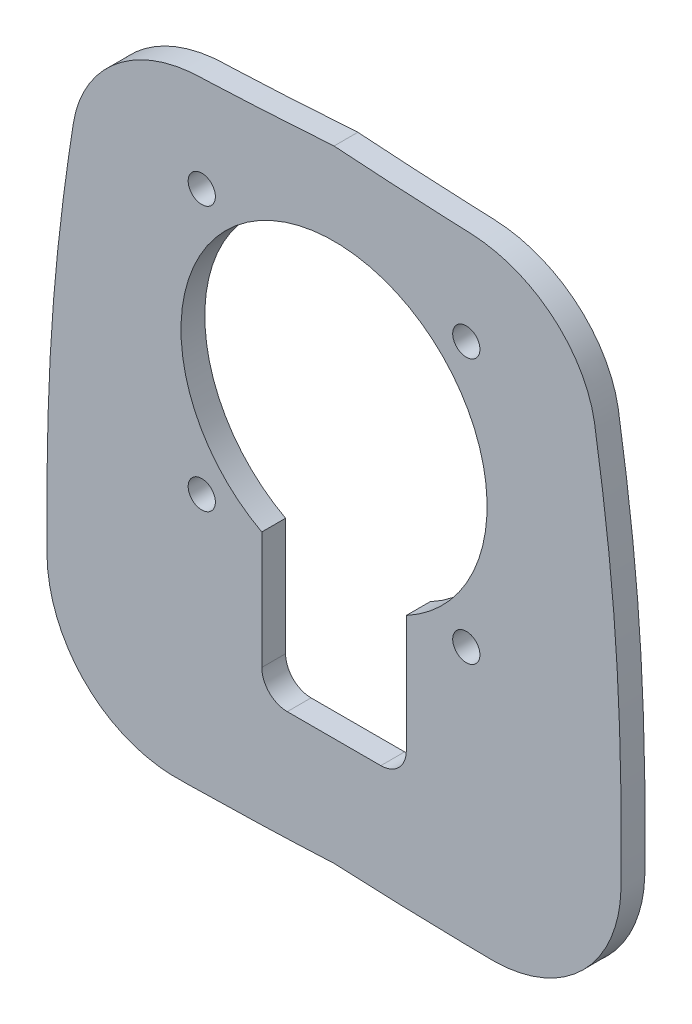
SolidWorks part; units mm, degrees
material "Фанера"
ref_plane "Front Plane" through (0, 0, 0) normal (0, 0, 1) x (1, 0, 0)
ref_plane "Top Plane" through (0, 0, 0) normal (0, 1, 0) x (1, 0, 0)
ref_plane "Right Plane" through (0, 0, 0) normal (1, 0, 0) x (0, 0, -1)
sketch "Эскиз1" plane through (0, 0, 0) normal (0, 0, 1) x (1, 0, 0)
  line L0 (-26.5384, 103.6369) -> (26.68, 103.6369) construction
  line L6 (5.5, 70.9713) -> (-5.5, 70.9713)
  line L7 (0, 125.3232) -> (-0.0007, 91.2257) construction
  line L8 (0, 114.735) -> (0, 139.0052) construction
  line L9 (-19.8938, 83.7432) -> (19.7424, 123.3793) construction
  line L10 (8.5, 73.9713) -> (8.5, 87.7703)
  line L12 (-8.5, 73.9713) -> (-8.5, 87.7703)
  line L13 (8.5, 70.9713) -> (0, 85.6369) construction
  line L14 (-0.0008, 85.6355) -> (-8.5, 70.9713) construction
  circle A1 centre (0, 103.6369) radius 4.3081 construction
  arc A2 (8.5, 87.7703) -> (-8.5, 87.7703) centre (0, 103.6369) ccw
  circle A6 centre (15.5563, 119.1933) radius 1.6
  circle A7 centre (-15.5566, 119.1939) radius 1.6
  circle A8 centre (15.5563, 88.0806) radius 1.6
  circle A9 centre (-15.5566, 88.0799) radius 1.6
  arc A10 (-5.5, 70.9713) -> (-8.5, 73.9713) centre (-5.5, 73.9713) cw
  arc A11 (5.5, 70.9713) -> (8.5, 73.9713) centre (5.5, 73.9713) ccw
  arc A12 (0, 85.6369) -> (-0.0008, 85.6369) centre (0, 103.6369) ccw
  spline S0 degree 3 poles (0, -5.0329) (0.0001, -4.9398) (0.0002, -4.7514) (0.0004, -4.4334) (0.0005, -4.0869) (0.0005, -3.7101) (0.0004, -3.3048) (0.0003, -2.8716) (0.0002, -2.4115) (0, -1.9253) (-0.0001, -1.4141) (-0.0002, -0.8785) (-0.0002, -0.3195) (-0.0002, 0.262) (-0.0002, 0.8651) (-0.0002, 1.4891) (-0.0001, 2.1331) (-0.0001, 2.7961) (-0.0001, 3.4773) (-0.0001, 4.1759) (-0.0001, 4.8909) (-0.0001, 5.6214) (-0.0002, 6.3667) (-0.0002, 7.1257) (-0.0002, 7.8977) (-0.0002, 8.6818) (-0.0003, 9.7444) (-0.0003, 11.0971) (-0.0003, 12.4734) (-0.0002, 13.5891) (0, 15.895) (0.0008, 19.6894) (-0.0004, 24.9437) (-0.0019, 29.9591) (0, 34.5228) (0.0041, 38.4701) (-0.0005, 42.291) (-0.006, 46.3858) (0.002, 51.3216) (0.0001, 56.9087) (-0.0003, 63.1461) (0.0003, 68.4854) (-0.0002, 72.6552) (-0.0004, 75.4314) (-0.0004, 78.2707) (0.0001, 81.1695) (0.0006, 84.1237) (0.0003, 87.1314) (-0.0013, 90.1821) (-0.0004, 92.2701) (0, 93.3097) knots 0 0 0 0 0.006162 0.012481 0.018955 0.025584 0.032367 0.0393 0.046381 0.053606 0.060972 0.068474 0.076108 0.083869 0.091751 0.099751 0.107861 0.116077 0.124392 0.132802 0.141299 0.149878 0.158532 0.167256 0.176042 0.184885 0.193777 0.211685 0.229714 0.238756 0.247808 0.303937 0.358537 0.40994 0.456468 0.496425 0.529358 0.574163 0.624121 0.680004 0.740385 0.803869 0.828231 0.852769 0.877416 0.902104 0.926769 0.951346 0.975776 1 1 1 1 construction
  spline S2 degree 3 poles (0, 59.0642) (0.4475, 59.0414) (1.3668, 58.9945) (2.783, 58.9312) (4.4611, 58.862) (6.3739, 58.7905) (8.2078, 58.7298) (9.7641, 58.6842) (11.2423, 58.6448) (12.9489, 58.6036) (14.5515, 58.5684) (15.8416, 58.5428) (16.7893, 58.5253) (17.7005, 58.5128) (18.5132, 58.4969) (19.2293, 58.5146) (19.8495, 58.5553) (20.567, 58.6306) (21.386, 58.7598) (22.9919, 59.1215) (24.9585, 59.8608) (27.1333, 61.1864) (28.7695, 62.5949) (30.1039, 64.1465) (31.1371, 65.7397) (31.9599, 67.4769) (32.4434, 68.9813) (32.7162, 70.2356) (32.8493, 71.12) (32.9396, 72.0815) (32.9586, 73.0644) (32.9652, 74.0787) (32.9713, 74.9562) (32.9744, 75.6726) (32.976, 76.23) (32.9767, 76.63) (32.9774, 77.5284) (32.9747, 78.8869) (32.9606, 80.8283) (32.937, 82.6986) (32.8662, 86.5294) (32.714, 91.0094) (32.4197, 96.1106) (32.1302, 99.9665) (31.7799, 103.7442) (31.3599, 107.5597) (30.8834, 111.3256) (30.5004, 114.0311) (30.261, 115.6402) (30.181, 116.1728) (30.0993, 116.7091) (30.0165, 117.2492) (29.9312, 117.7929) (29.848, 118.3428) (29.7266, 118.9603) (29.5244, 119.7599) (29.2093, 120.6961) (28.7987, 121.6366) (28.0749, 123.0055) (26.8651, 124.6888) (24.9879, 126.458) (23.0416, 127.741) (21.143, 128.6265) (19.5847, 129.1273) (18.3088, 129.4102) (17.3274, 129.5622) (16.3878, 129.6517) (15.337, 129.6872) (14.1707, 129.7357) (12.88, 129.7907) (11.383, 129.8592) (9.6708, 129.9429) (7.7302, 130.0452) (5.7954, 130.1541) (3.8724, 130.2699) (1.9443, 130.3933) (0.6556, 130.4826) (0, 130.528) knots 0 0 0 0 0.011004 0.022608 0.034816 0.052254 0.069618 0.079881 0.090495 0.105935 0.121808 0.129865 0.137625 0.145087 0.152247 0.157586 0.162674 0.167508 0.175302 0.18302 0.207923 0.226441 0.245338 0.26069 0.276561 0.291825 0.307773 0.315244 0.323334 0.329724 0.338948 0.347464 0.354641 0.3605 0.365058 0.36833 0.370324 0.387123 0.401694 0.418008 0.433059 0.495795 0.528084 0.558547 0.590759 0.621256 0.652817 0.683984 0.688362 0.692772 0.697213 0.701685 0.706191 0.710731 0.715341 0.721643 0.730976 0.739566 0.746816 0.768987 0.790087 0.809834 0.825978 0.841402 0.849928 0.858055 0.865776 0.873092 0.883874 0.894446 0.904821 0.920679 0.936548 0.952549 0.968273 0.98386 1 1 1 1 construction
  spline S3 degree 3 poles (0, 130.528) (-0.6336, 130.4841) (-1.8796, 130.3977) (-4.3725, 130.2376) (-7.4791, 130.0556) (-10.5899, 129.8957) (-13.0857, 129.7809) (-14.5257, 129.7213) (-15.5476, 129.68) (-16.1421, 129.6603) (-16.755, 129.6179) (-17.3855, 129.5496) (-18.0324, 129.4533) (-19.0764, 129.2531) (-20.5153, 128.8557) (-22.798, 127.9125) (-25.4829, 126.1759) (-27.5794, 123.8358) (-28.8609, 121.586) (-29.409, 120.178) (-29.7007, 119.0728) (-29.8302, 118.449) (-29.9391, 117.7422) (-30.066, 116.9294) (-30.3526, 115.0436) (-30.7644, 112.2005) (-31.2544, 108.4352) (-31.6892, 104.6219) (-32.0542, 100.8484) (-32.3593, 96.9982) (-32.673, 91.9045) (-32.8647, 86.7657) (-32.9568, 81.6639) (-32.9776, 78.5908) (-32.9769, 76.0383) (-32.9694, 74.4715) (-32.9576, 73.2135) (-32.9525, 72.5756) (-32.921, 71.883) (-32.8504, 71.1136) (-32.6721, 69.9709) (-32.3626, 68.6894) (-31.7555, 66.9808) (-30.8186, 65.1598) (-29.5171, 63.4003) (-28.0807, 61.9653) (-26.5465, 60.8039) (-24.8781, 59.8675) (-23.3864, 59.2777) (-22.1582, 58.929) (-21.2297, 58.7308) (-20.2842, 58.5924) (-19.4117, 58.5206) (-18.598, 58.4973) (-17.8556, 58.5101) (-17.0829, 58.5206) (-16.2802, 58.5347) (-15.4218, 58.5508) (-14.5, 58.5699) (-13.5275, 58.5912) (-12.5521, 58.6135) (-11.2502, 58.6447) (-9.6457, 58.6869) (-7.7127, 58.7453) (-5.7941, 58.8115) (-3.8398, 58.8867) (-1.9087, 58.9681) (-0.6213, 59.0329) (0, 59.0642) knots 0 0 0 0 0.015599 0.030679 0.061356 0.092035 0.107185 0.122722 0.127436 0.132303 0.137332 0.142524 0.147877 0.15339 0.168629 0.184445 0.213919 0.246382 0.260434 0.277385 0.283294 0.288498 0.293024 0.300857 0.308706 0.339874 0.371416 0.401967 0.43414 0.464527 0.496828 0.559482 0.590814 0.622156 0.634964 0.653509 0.66064 0.665867 0.669174 0.677668 0.684827 0.697568 0.709981 0.729296 0.747627 0.76351 0.779012 0.794745 0.810358 0.818285 0.826084 0.83366 0.841742 0.847571 0.853649 0.859976 0.866551 0.87337 0.881062 0.889199 0.897261 0.905027 0.921185 0.936683 0.952526 0.96834 0.98472 1 1 1 1 construction
  spline S4 degree 1 poles (0, 131.3299) (-0.0002, 58.2631) knots 0 0 1 1 construction
  spline S5 degree 1 poles (-0.0002, 58.2631) (0, 131.3299) knots 0 0 1 1 construction
  spline S6 degree 3 poles (0, 131.3299) (-1.2676, 131.2421) (-3.8032, 131.071) (-7.6078, 130.8502) (-10.7803, 130.6862) (-13.3179, 130.5732) (-14.9044, 130.5017) (-16.1757, 130.4639) (-17.5223, 130.359) (-19.8224, 129.9638) (-22.995, 128.8088) (-26.3478, 126.4966) (-28.539, 123.8821) (-29.792, 121.4757) (-30.3439, 119.8779) (-30.634, 118.5334) (-30.8186, 117.2662) (-31.0655, 115.6934) (-31.3404, 113.7989) (-31.694, 111.2714) (-32.263, 106.8394) (-32.9231, 100.4874) (-33.4439, 92.8412) (-33.6731, 86.4629) (-33.7607, 81.3617) (-33.7784, 78.1723) (-33.7769, 75.625) (-33.7621, 74.025) (-33.7594, 72.7621) (-33.7048, 71.4079) (-33.3763, 69.0902) (-32.2747, 65.8831) (-29.9808, 62.5161) (-26.8627, 59.8884) (-23.7749, 58.4811) (-21.1512, 57.8724) (-19.4841, 57.7045) (-18.1426, 57.7019) (-16.8844, 57.7253) (-14.6423, 57.7632) (-11.4667, 57.8366) (-6.3673, 57.9784) (-2.5466, 58.135) (-0.0002, 58.2631) knots -0.000454 -0.000454 -0.000454 -0.000454 0.0308 0.062054 0.093308 0.108935 0.124562 0.132375 0.140189 0.155815 0.187069 0.218323 0.249577 0.265204 0.280831 0.288644 0.296458 0.312084 0.327711 0.343338 0.374592 0.4371 0.499607 0.562115 0.593369 0.624623 0.640249 0.655876 0.66369 0.671503 0.68713 0.718384 0.749638 0.780892 0.812145 0.827772 0.843399 0.851213 0.859026 0.874653 0.905907 0.937161 0.999668 0.999668 0.999668 0.999668
  spline S7 degree 3 poles (-0.0002, 58.2631) (2.5464, 58.1334) (6.3679, 57.9786) (11.4674, 57.8367) (14.644, 57.7625) (16.8851, 57.7264) (18.1452, 57.701) (19.4846, 57.7052) (21.1532, 57.8726) (23.7771, 58.4819) (26.8697, 59.8927) (29.9867, 62.5219) (32.2781, 65.8925) (33.377, 69.0874) (33.7543, 71.7647) (33.7616, 73.7308) (33.7763, 75.6279) (33.7788, 78.183) (33.7604, 81.3689) (33.6729, 86.4721) (33.4434, 92.8501) (32.9223, 100.4972) (32.2619, 106.8496) (31.6925, 111.282) (31.339, 113.8095) (31.0637, 115.7047) (30.8176, 117.2761) (30.6317, 118.5474) (30.3408, 119.8883) (29.7877, 121.4863) (28.5328, 123.8902) (26.343, 126.5002) (22.9984, 128.807) (19.8234, 129.9632) (17.5249, 130.3591) (16.1763, 130.4635) (14.9044, 130.5016) (13.3195, 130.5732) (10.7809, 130.6861) (7.6085, 130.8502) (3.8036, 131.0709) (1.2677, 131.2421) (0, 131.3299) knots 0.000332 0.000332 0.000332 0.000332 0.062839 0.094093 0.125347 0.140974 0.148787 0.156601 0.172228 0.187855 0.219108 0.250362 0.281616 0.31287 0.328497 0.344124 0.359751 0.375377 0.406631 0.437885 0.500393 0.5629 0.625408 0.656662 0.672289 0.687915 0.703542 0.711356 0.719169 0.734796 0.750423 0.781677 0.812931 0.844185 0.859811 0.867625 0.875438 0.891065 0.906692 0.937946 0.9692 1.000454 1.000454 1.000454 1.000454
  point P7 (0, 85.6369)
  point P20 (0, 85.6369)
  dimension "D2" = 36
  dimension "D7" = 3.2
  dimension "D5" = 3
  dimension "D3" = 17
  dimension "D6" = 45
  dimension "D8" = 22
  dimension "D1" = 0.8
extrude "Бобышка-Вытянуть1" add sketch "Эскиз1" along normal mid plane 2.8 contours S6 S7 A8 A6 A7 A9 A11 L6 A10 L12 A2 L10
